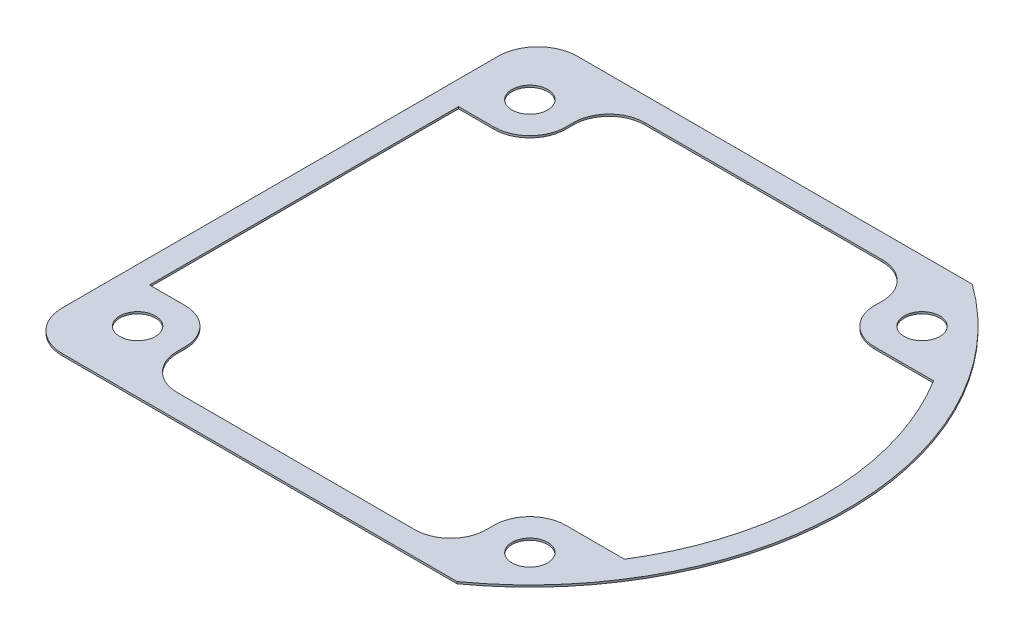
SolidWorks part; units mm, degrees
ref_plane "Front Plane" through (0, 0, 0) normal (0, 0, 1) x (1, 0, 0)
ref_plane "Top Plane" through (0, 0, 0) normal (0, 1, 0) x (1, 0, 0)
ref_plane "Right Plane" through (0, 0, 0) normal (1, 0, 0) x (0, 0, -1)
sketch "Sketch1" plane through (0, 0, 0) normal (0, 1, 0) x (1, 0, 0)
  line L1 (-63, 65) -> (46.6369, 65)
  line L2 (-63, 65) -> (-63, -65)
  line L3 (-63, -65) -> (46.6369, -65)
  arc A3 (46.6369, -65) -> (46.6369, 65) centre (0, 0) ccw
  point P0 (0, 0)
  point P4 (80, 0)
  dimension "D4" = 160
  dimension "D1" = 130
  dimension "D2" = 143
extrude "Boss-Extrude1" add sketch "Sketch1" along normal blind 0.5
fillet "Fillet1" radius 10 2 edges at (-63, 0.25, -65) (-63, 0.25, 65)
sketch "Sketch27" plane through (0, 0.5, 0) normal (0, 1, 0) x (1, 0, 0)
  circle A1 centre (49.4975, -49.4975) radius 4.5
  circle A2 centre (-49.4975, -49.4975) radius 4.5
  circle A3 centre (-49.4975, 49.4975) radius 4.5
  circle A4 centre (49.4975, 49.4975) radius 4.5
  point P19 (0, 0)
  dimension "D1" = 4
extrude "Cut-Extrude9" cut sketch "Sketch27" along direction (0, 1, 0) on the side against the normal through all contours A2 | A1 | A4 | A3
sketch "Sketch36" plane through (0, 0.5, 0) normal (0, 1, 0) x (1, 0, 0)
sketch "Sketch39" plane through (0, 0, 0) normal (0, -1, 0) x (1, 0, 0)
sketch "Sketch44" plane through (0, 0.5, 0) normal (0, 1, 0) x (1, 0, 0)
  line L0 (47.9975, 38.9975) -> (62.8904, 38.9975)
  line L2 (47.9975, -38.9975) -> (62.8904, -38.9975)
  line L6 (38.9975, 47.9975) -> (38.9975, 50)
  line L8 (38.9975, -47.9975) -> (38.9975, -50)
  line L12 (29.9975, 59) -> (-29.9975, 59)
  line L13 (-57, 38.9975) -> (-57, -38.9975)
  line L17 (-38.9975, -47.9975) -> (-38.9975, -50)
  line L18 (-47.9975, -38.9975) -> (-57, -38.9975)
  line L19 (-47.9975, 38.9975) -> (-57, 38.9975)
  line L20 (-38.9975, 47.9975) -> (-38.9975, 50)
  line L22 (-29.9975, -59) -> (29.9975, -59)
  arc A5 (47.9975, 38.9975) -> (38.9975, 47.9975) centre (47.9975, 47.9975) cw
  arc A6 (38.9975, 50) -> (29.9975, 59) centre (29.9975, 50) ccw
  arc A7 (47.9975, -38.9975) -> (38.9975, -47.9975) centre (47.9975, -47.9975) ccw
  arc A13 (62.8904, -38.9975) -> (62.8904, 38.9975) centre (0, 0) ccw
  arc A14 (38.9975, -50) -> (29.9975, -59) centre (29.9975, -50) cw
  arc A15 (-38.9975, -50) -> (-29.9975, -59) centre (-29.9975, -50) ccw
  arc A16 (-47.9975, -38.9975) -> (-38.9975, -47.9975) centre (-47.9975, -47.9975) cw
  arc A17 (-47.9975, 38.9975) -> (-38.9975, 47.9975) centre (-47.9975, 47.9975) ccw
  arc A18 (-38.9975, 50) -> (-29.9975, 59) centre (-29.9975, 50) cw
extrude "Cut-Extrude17" cut sketch "Sketch44" against normal through all
equation "\"9.29.20727427cm\"=9.20727"
